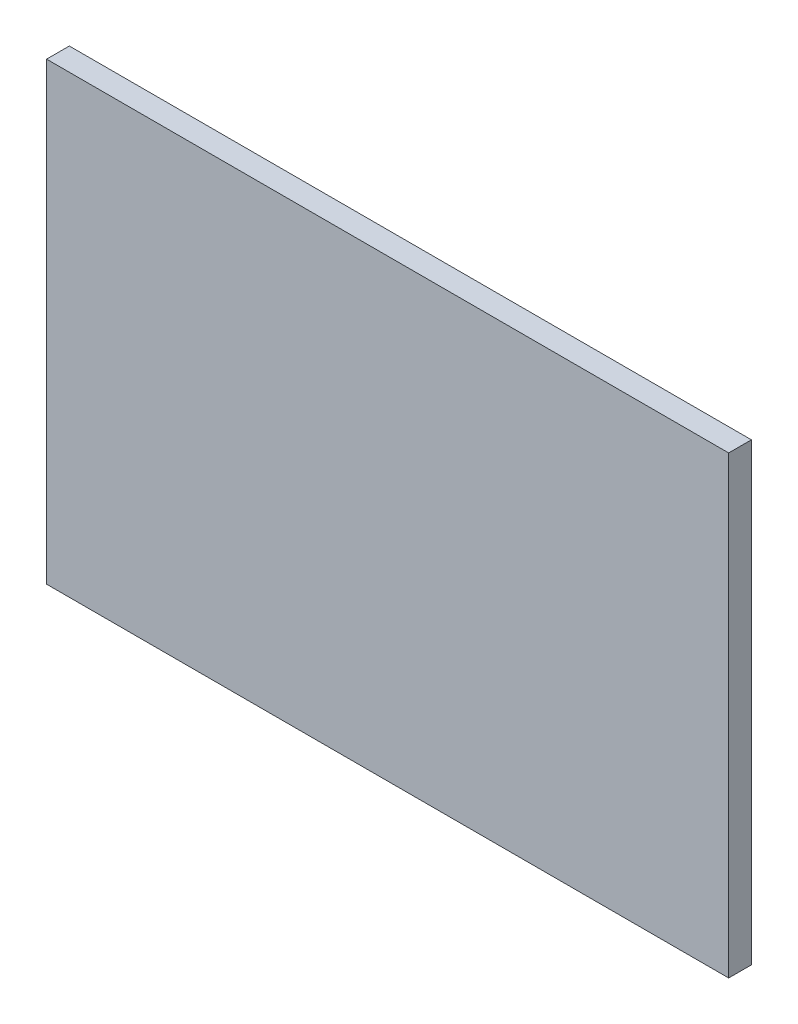
SolidWorks part; units mm, degrees
ref_plane "Front Plane" through (0, 0, 0) normal (0, 0, 1) x (1, 0, 0)
ref_plane "Top Plane" through (0, 0, 0) normal (0, 1, 0) x (1, 0, 0)
ref_plane "Right Plane" through (0, 0, 0) normal (1, 0, 0) x (0, 0, -1)
sketch "Sketch2" plane through (0, 0, 0) normal (0, 0, 1) x (1, 0, 0)
  line L1 (0, 0) -> (750, 0)
  line L2 (0, 0) -> (0, 500)
  line L3 (0, 500) -> (750, 500)
  line L4 (750, 0) -> (750, 500)
  dimension "D1" = 750
  dimension "D2" = 500
extrude "base" add sketch "Sketch2" along normal blind 25
